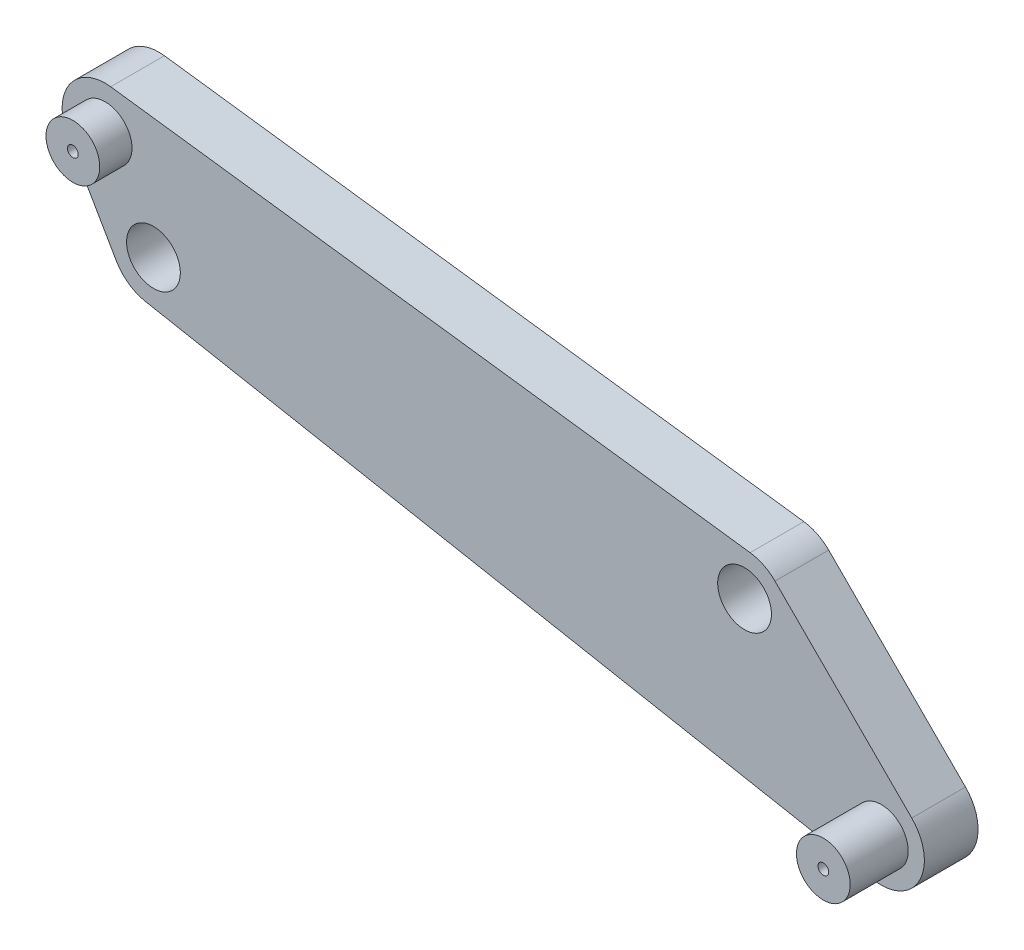
SolidWorks part; units mm, degrees
material "ABS"
ref_plane "Front Plane" through (0, 0, 0) normal (0, 0, 1) x (1, 0, 0)
ref_plane "Top Plane" through (0, 0, 0) normal (0, 1, 0) x (1, 0, 0)
ref_plane "Right Plane" through (0, 0, 0) normal (1, 0, 0) x (0, 0, -1)
sketch "Sketch1" plane through (0, 0, 0) normal (0, 0, 1) x (1, 0, 0)
  line L0 (0, 0) -> (-55, 0)
  line L1 (-55, 0) -> (-59.5, 7.7942)
  line L2 (0, 0) -> (12.7279, -12.7279)
  dimension "D1" = 55
  dimension "D2" = 9
  dimension "D3" = 18
  dimension "D4" = 120
  dimension "D5" = 135
sketch "Sketch2" plane through (0, 0, 0) normal (0, 0, 1) x (1, 0, 0)
  line L0 (-58.9805, 11.7603) -> (0.5195, 3.9661)
  line L1 (2.8284, 2.8284) -> (15.5563, -9.8995)
  line L2 (11.9891, -16.6591) -> (-55.7388, -3.9312)
  line L3 (-58.4641, -2) -> (-62.9641, 5.7942)
  circle A0 centre (-55, 0) radius 2.5
  circle A1 centre (-59.5, 7.7942) radius 2.5
  arc A2 (-58.9805, 11.7603) -> (-62.9641, 5.7942) centre (-59.5, 7.7942) ccw
  arc A3 (-58.4641, -2) -> (-55.7388, -3.9312) centre (-55, 0) ccw
  circle A4 centre (0, 0) radius 2.5
  circle A5 centre (12.7279, -12.7279) radius 2.5
  arc A6 (2.8284, 2.8284) -> (0.5195, 3.9661) centre (0, 0) ccw
  arc A7 (11.9891, -16.6591) -> (15.5563, -9.8995) centre (12.7279, -12.7279) ccw
  dimension "D1" = 5
  dimension "D2" = 5
  dimension "D3" = 5
  dimension "D4" = 5
  dimension "D5" = 8
  dimension "D6" = 8
  dimension "D7" = 8
  dimension "D8" = 8
extrude "Boss-Extrude1" add sketch "Sketch2" along normal blind 5
sketch "Sketch4" plane through (0, 0, 0) normal (0, 0, -1) x (-1, 0, 0)
  circle A0 centre (59.5, 7.7942) radius 2.5
  circle A1 centre (59.5, 7.7942) radius 0.5
  circle A2 centre (-12.7279, -12.7279) radius 2.5
  circle A3 centre (-12.7279, -12.7279) radius 0.5
  dimension "D1" = 1
  dimension "D2" = 5
  dimension "D3" = 5
  dimension "D4" = 1
extrude "Boss-Extrude3" add sketch "Sketch4" against normal blind 8
sketch "Sketch5" plane through (0, 0, 8) normal (0, 0, 1) x (1, 0, 0)
  circle A0 centre (12.7279, -12.7279) radius 2.5
  circle A1 centre (12.7279, -12.7279) radius 0.5
  dimension "D1" = 5
  dimension "D2" = 1
extrude "Boss-Extrude4" add sketch "Sketch5" along normal blind 2.4
